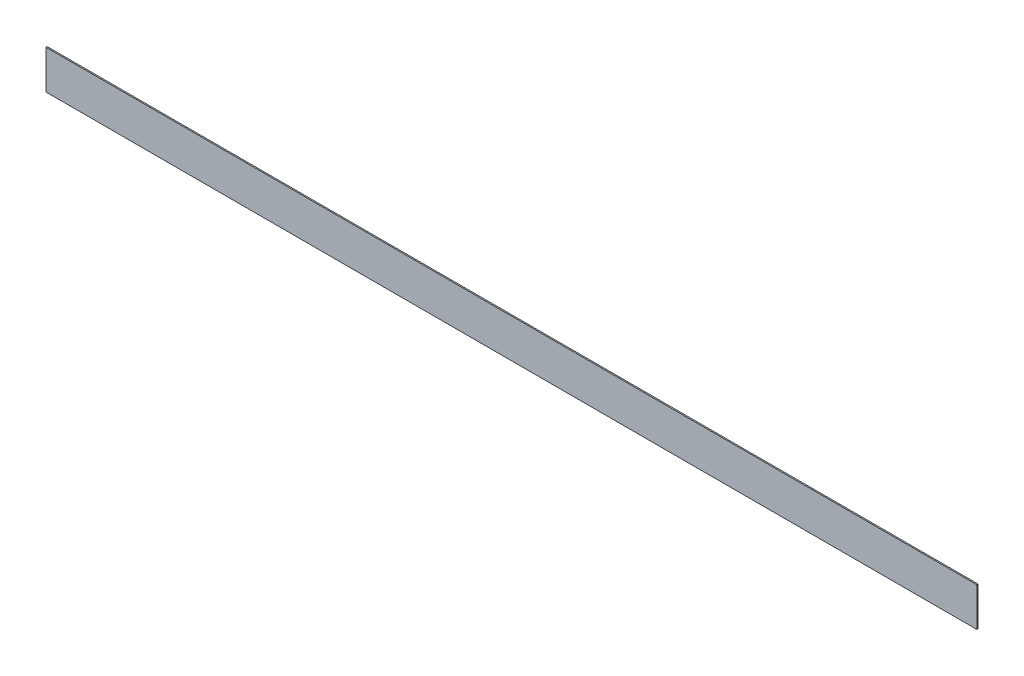
SolidWorks part; units mm, degrees
material "Nylon 101"
ref_plane "Front Plane" through (0, 0, 0) normal (0, 0, 1) x (1, 0, 0)
ref_plane "Top Plane" through (0, 0, 0) normal (0, 1, 0) x (1, 0, 0)
ref_plane "Right Plane" through (0, 0, 0) normal (1, 0, 0) x (0, 0, -1)
sketch "Sketch1" plane through (0, 0, 0) normal (0, 0, 1) x (1, 0, 0)
  line L6 (0, 0) -> (-1219.2, 0)
  line L7 (0, 0) -> (0, -50.8)
  line L8 (0, -50.8) -> (-1219.2, -50.8)
  line L9 (-1219.2, 0) -> (-1219.2, -50.8)
  dimension "D1" = 50.8
  dimension "D2" = 1219.2
extrude "Boss-Extrude1" add sketch "Sketch1" along normal blind 1.5875
